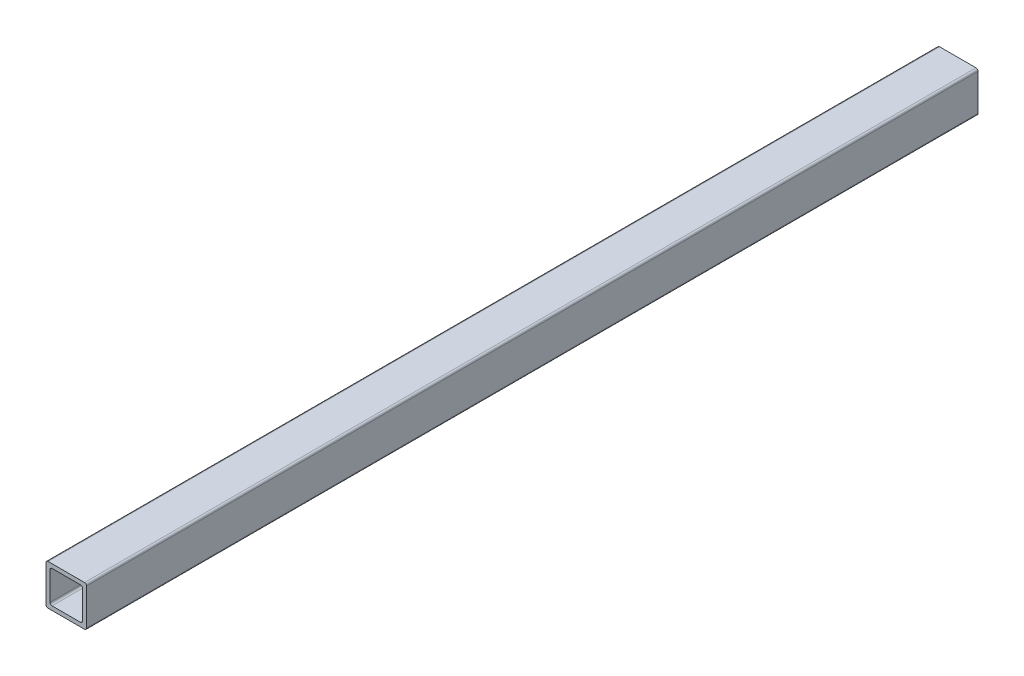
SolidWorks part; units mm, degrees
ref_plane "Plan de face" through (0, 0, 0) normal (0, 0, 1) x (1, 0, 0)
ref_plane "Plan de dessus" through (0, 0, 0) normal (0, 1, 0) x (1, 0, 0)
ref_plane "Plan de droite" through (0, 0, 0) normal (1, 0, 0) x (0, 0, -1)
sketch "Esquisse2" plane through (0, 0, 0) normal (0, 0, 1) x (1, 0, 0)
  line L0 (6, 4) -> (34, 4)
  line L1 (2, 0) -> (38, 0)
  line L2 (0, 2) -> (0, 38)
  line L3 (2, 40) -> (38, 40)
  line L4 (40, 2) -> (40, 38)
  line L5 (36, 6) -> (36, 34)
  line L6 (6, 36) -> (34, 36)
  line L7 (4, 6) -> (4, 34)
  line L8 (4, 4) -> (36, 4) construction
  line L9 (36, 4) -> (36, 36) construction
  line L10 (4, 36) -> (36, 36) construction
  line L11 (4, 4) -> (4, 36) construction
  line L12 (0, 0) -> (40, 0) construction
  line L13 (0, 0) -> (0, 40) construction
  line L14 (0, 40) -> (40, 40) construction
  line L15 (40, 0) -> (40, 40) construction
  arc A0 (34, 4) -> (36, 6) centre (34, 6) ccw
  arc A1 (36, 34) -> (34, 36) centre (34, 34) ccw
  arc A2 (6, 36) -> (4, 34) centre (6, 34) ccw
  arc A3 (4, 6) -> (6, 4) centre (6, 6) ccw
  arc A4 (2, 0) -> (0, 2) centre (2, 2) cw
  arc A5 (0, 38) -> (2, 40) centre (2, 38) cw
  arc A6 (38, 40) -> (40, 38) centre (38, 38) cw
  arc A7 (40, 2) -> (38, 0) centre (38, 2) cw
  point P24 (0, 0)
  dimension "D4" = 2
  dimension "D1" = 40
  dimension "D2" = 40
  dimension "D3" = 4
extrude "Boss.-Extru.1" add sketch "Esquisse2" along normal blind 880
